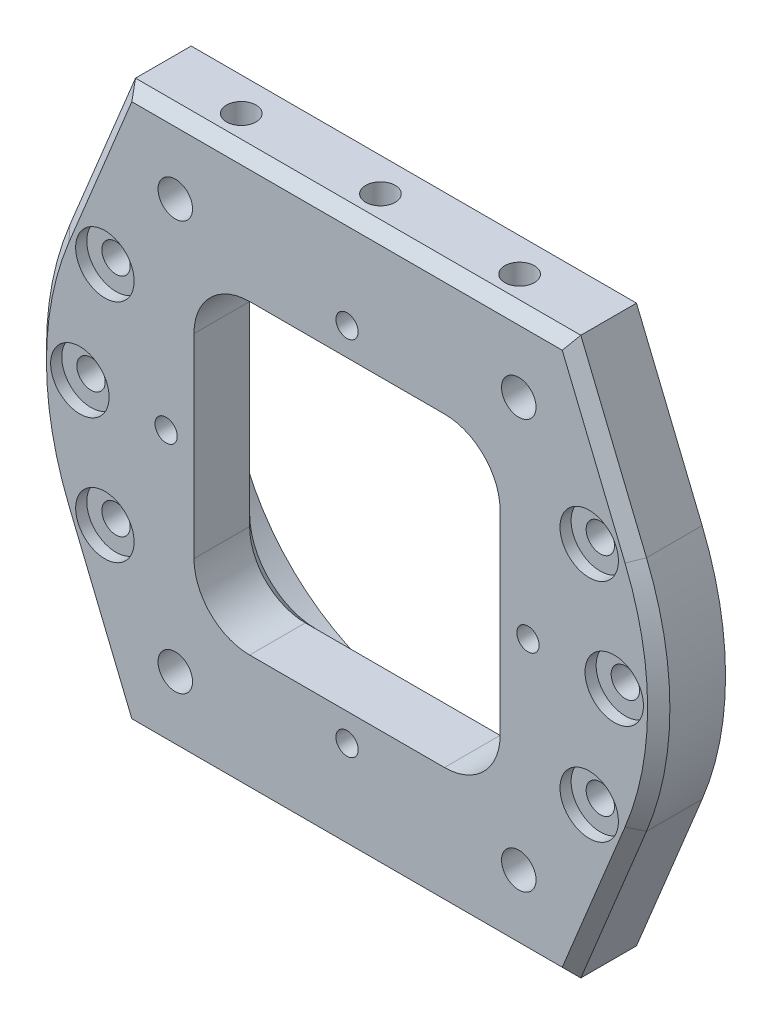
SolidWorks part; units mm, degrees
ref_plane "Спереди" through (0, 0, 0) normal (0, 0, 1) x (1, 0, 0)
ref_plane "Сверху" through (0, 0, 0) normal (0, 1, 0) x (1, 0, 0)
ref_plane "Справа" through (0, 0, 0) normal (1, 0, 0) x (0, 0, -1)
other "Configuration Table"
sketch "Эскиз2" plane through (0, 0, 0) normal (0, 0, 1) x (1, 0, 0)
  line L0 (0, 0) -> (0, -62.4857) construction
  line L2 (0, 27.5143) -> (0, 0) construction
  line L4 (5, 0) -> (-5, 0) construction
  line L6 (-130.3444, 0) -> (-32.1778, 0) construction
  line L10 (40, 50) -> (-40, 50)
  line L11 (-40, -50) -> (40, -50)
  line L12 (-51.7989, 21.2809) -> (-40, 50)
  line L13 (-51.7989, -21.2809) -> (-40, -50)
  line L14 (51.7989, -21.2809) -> (40, -50)
  line L15 (51.7989, 21.2809) -> (40, 50)
  arc A13 (-51.7989, 21.2809) -> (-51.7989, -21.2809) centre (0, 0) ccw
  arc A15 (51.7989, 21.2809) -> (51.7989, -21.2809) centre (0, 0) cw
  point P6 (0, -50)
  point P10 (0, 50)
  dimension "D5" = 50
  dimension "D4" = 56
  dimension "D1" = 5
  dimension "D2" = 40
  dimension "D3" = 50
extrude "Бобышка-Вытянуть1" add sketch "Эскиз2" along normal blind 12
sketch "Эскиз3" plane through (0, 50, 0) normal (0, 1, 0) x (1, 0, 0)
  line L0 (-25, -6) -> (0, -6) construction
  line L1 (0, -6) -> (25, -6) construction
  line L2 (0, -6) -> (0, 0) construction
  line L3 (0, -6) -> (0, -12) construction
  line L4 (40, -12) -> (-40, -12) construction
  circle A0 centre (-25, -6) radius 2.65
  circle A1 centre (0, -6) radius 2.65
  circle A2 centre (25, -6) radius 2.65
  dimension "D2" = 5.3
  dimension "D1" = 25
extrude "Вырез-Вытянуть1" cut sketch "Эскиз3" against normal blind 8
mirror "Зеркальное отражение1" about plane through (0, 0, 0) normal (0, 1, 0) of "Вырез-Вытянуть1"
sketch "Эскиз5" plane through (0, 0, 12) normal (0, 0, 1) x (1, 0, 0)
  line L0 (-30.8538, 36.7701) -> (0, 0) construction
  line L1 (0, 0) -> (-43.5028, 20.2857) construction
  line L2 (-48, 0) -> (0, 0) construction
  line L3 (-43.5028, -20.2857) -> (0, 0) construction
  line L4 (-30.8538, -36.7701) -> (0, 0) construction
  line L5 (0, 0) -> (0, 38.3521) construction
  circle A0 centre (-48, 0) radius 2.55
  circle A1 centre (-43.5028, 20.2857) radius 2.55
  circle A2 centre (-43.5028, -20.2857) radius 2.55
  circle A3 centre (-30.8538, -36.7701) radius 3.1
  circle A4 centre (-30.8538, 36.7701) radius 3.1
  circle A5 centre (30.8538, 36.7701) radius 3.1
  circle A6 centre (30.8538, -36.7701) radius 3.1
  circle A7 centre (43.5028, -20.2857) radius 2.55
  circle A8 centre (43.5028, 20.2857) radius 2.55
  circle A9 centre (48, 0) radius 2.55
  dimension "D1" = 5.1
  dimension "D2" = 6.2
  dimension "D3" = 25
  dimension "D4" = 25
  dimension "D5" = 25
  dimension "D6" = 25
  dimension "D7" = 48
extrude "Вырез-Вытянуть2" cut sketch "Эскиз5" against normal through all
sketch "Эскиз7" plane through (0, 0, 12) normal (0, 0, 1) x (1, 0, 0)
  circle A0 centre (-43.5028, 20.2857) radius 5.25
  circle A1 centre (-48, 0) radius 5.25
  circle A2 centre (-43.5028, -20.2857) radius 5.25
  circle A3 centre (43.5028, 20.2857) radius 5.25
  circle A4 centre (48, 0) radius 5.25
  circle A5 centre (43.5028, -20.2857) radius 5.25
  dimension "D1" = 10.5
extrude "Вырез-Вытянуть3" cut sketch "Эскиз7" against normal blind 2
chamfer "Фаска3" distance 2 angle 45 8 edges at (-45.8994, 35.6405, 12) (0, 50, 12) (45.8994, 35.6405, 12) (56, 0, 12) (45.8994, -35.6405, 12) (0, -50, 12) (-45.8994, -35.6405, 12) (-56, 0, 12)
sketch "Эскиз8" plane through (0, 0, 12) normal (0, 0, 1) x (1, 0, 0)
  line L1 (-17.5, -27.5) -> (17.5, -27.5)
  line L2 (-27.5, -17.5) -> (-27.5, 17.5)
  line L3 (-17.5, 27.5) -> (17.5, 27.5)
  line L4 (27.5, -17.5) -> (27.5, 17.5)
  line L5 (-27.5, -27.5) -> (27.5, 27.5) construction
  line L6 (-27.5, 27.5) -> (27.5, -27.5) construction
  arc A1 (17.5, 27.5) -> (27.5, 17.5) centre (17.5, 17.5) cw
  arc A2 (17.5, -27.5) -> (27.5, -17.5) centre (17.5, -17.5) ccw
  arc A3 (-17.5, -27.5) -> (-27.5, -17.5) centre (-17.5, -17.5) cw
  arc A4 (-27.5, 17.5) -> (-17.5, 27.5) centre (-17.5, 17.5) cw
  point P0 (0, 0)
  dimension "D1" = 55
  dimension "D2" = 10
extrude "Вырез-Вытянуть4" cut sketch "Эскиз8" against normal up to surface (12 mm away) up to face at (-40.9528, 20.2857, 0)
sketch "Эскиз9" plane through (0, 0, 0) normal (0, 0, -1) x (-1, 0, 0)
  circle A0 centre (0, 0) radius 39.85
  circle A1 centre (0, 0) radius 36.85
  dimension "D1" = 79.7
  dimension "D2" = 3
extrude "Бобышка-Вытянуть2" add sketch "Эскиз9" along normal blind 4
sketch "Эскиз10" plane through (0, 0, 12) normal (0, 0, 1) x (1, 0, 0)
  circle A0 centre (0, 0) radius 32.5 construction
  circle A1 centre (0, 32.5) radius 2
  circle A2 centre (32.5, 0) radius 2
  circle A3 centre (0, -32.5) radius 2
  circle A4 centre (-32.5, 0) radius 2
  point P13 (0, 0)
  dimension "D1" = 65
  dimension "D2" = 4
  dimension "D3" = 4
extrude "Вырез-Вытянуть5" cut sketch "Эскиз10" against normal blind 8
chamfer "Фаска4" distance 2 angle 45 8 edges at (0, -27.5, 0) (-24.5711, -24.5711, 0) (24.5711, -24.5711, 0) (-27.5, 0, 0) (27.5, 0, 0) (-24.5711, 24.5711, 0) (24.5711, 24.5711, 0) (0, 27.5, 0)
chamfer "Фаска5" distance 0.5 angle 45 1 edges at (-39.85, 0, -4)
